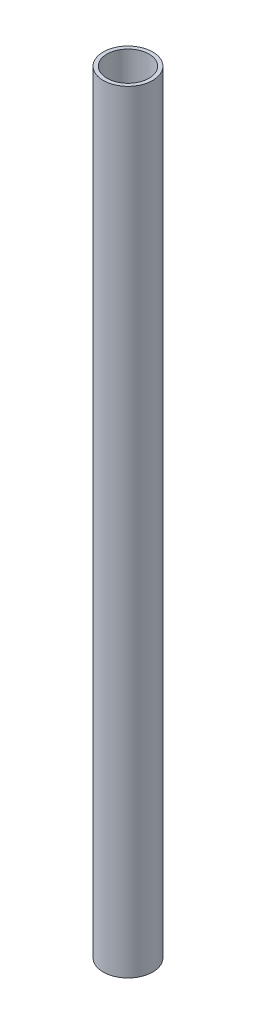
SolidWorks part; units mm, degrees
ref_plane "前视基准面" through (0, 0, 0) normal (0, 0, 1) x (1, 0, 0)
ref_plane "上视基准面" through (0, 0, 0) normal (0, 1, 0) x (1, 0, 0)
ref_plane "右视基准面" through (0, 0, 0) normal (1, 0, 0) x (0, 0, -1)
other "Configuration Table"
sketch "草图1" plane through (0, 0, 0) normal (0, 1, 0) x (1, 0, 0)
  circle A14 centre (0, 0) radius 16
  circle A15 centre (0, 0) radius 13.6
  dimension "D1" = 32
  dimension "D2" = 2.4
extrude "凸台-拉伸1" add sketch "草图1" along normal blind 500
